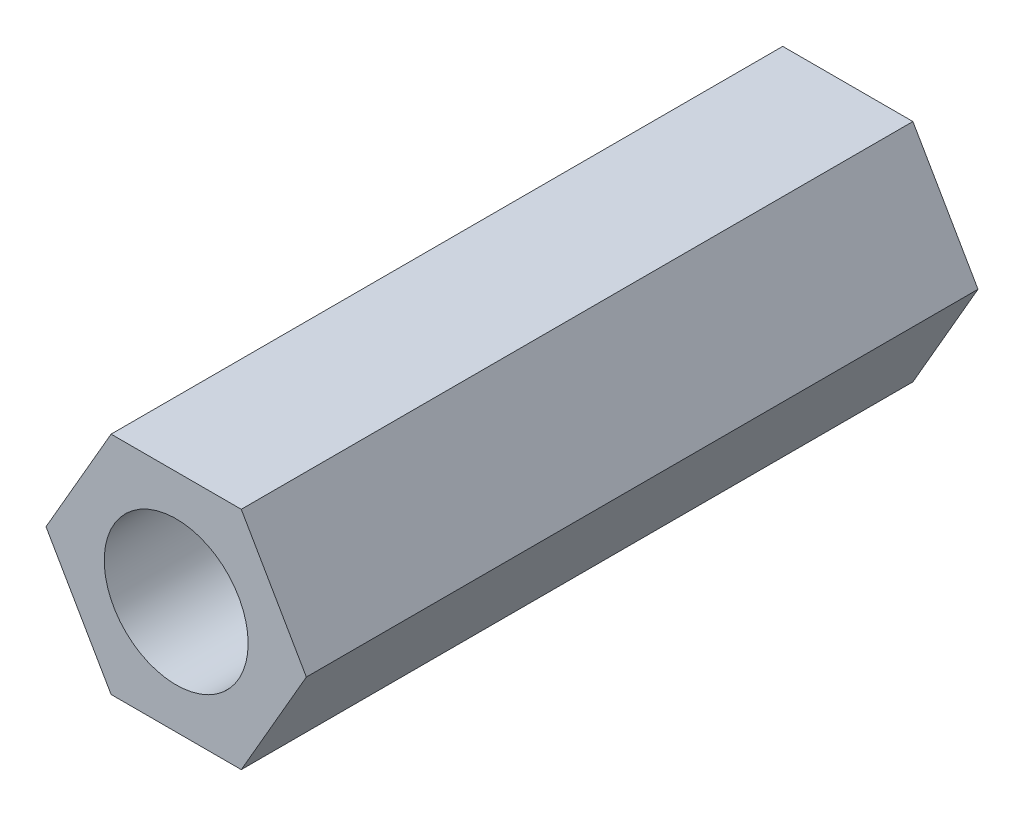
SolidWorks part; units mm, degrees
ref_plane "前视基准面" through (0, 0, 0) normal (0, 0, 1) x (1, 0, 0)
ref_plane "上视基准面" through (0, 0, 0) normal (0, 1, 0) x (1, 0, 0)
ref_plane "右视基准面" through (0, 0, 0) normal (1, 0, 0) x (0, 0, -1)
sketch "草图1" plane through (0, 0, 0) normal (0, 0, 1) x (1, 0, 0)
  line L1 (1.3568, 2.35) -> (-1.3568, 2.35)
  line L2 (-1.3568, 2.35) -> (-2.7135, 0)
  line L3 (-2.7135, 0) -> (-1.3568, -2.35)
  line L4 (-1.3568, -2.35) -> (1.3568, -2.35)
  line L5 (1.3568, -2.35) -> (2.7135, 0)
  line L6 (2.7135, 0) -> (1.3568, 2.35)
  circle A0 centre (0, 0) radius 1.5
  circle A1 centre (0, 0) radius 2.35 construction
extrude "凸台-拉伸1" add sketch "草图1" along normal blind 14
